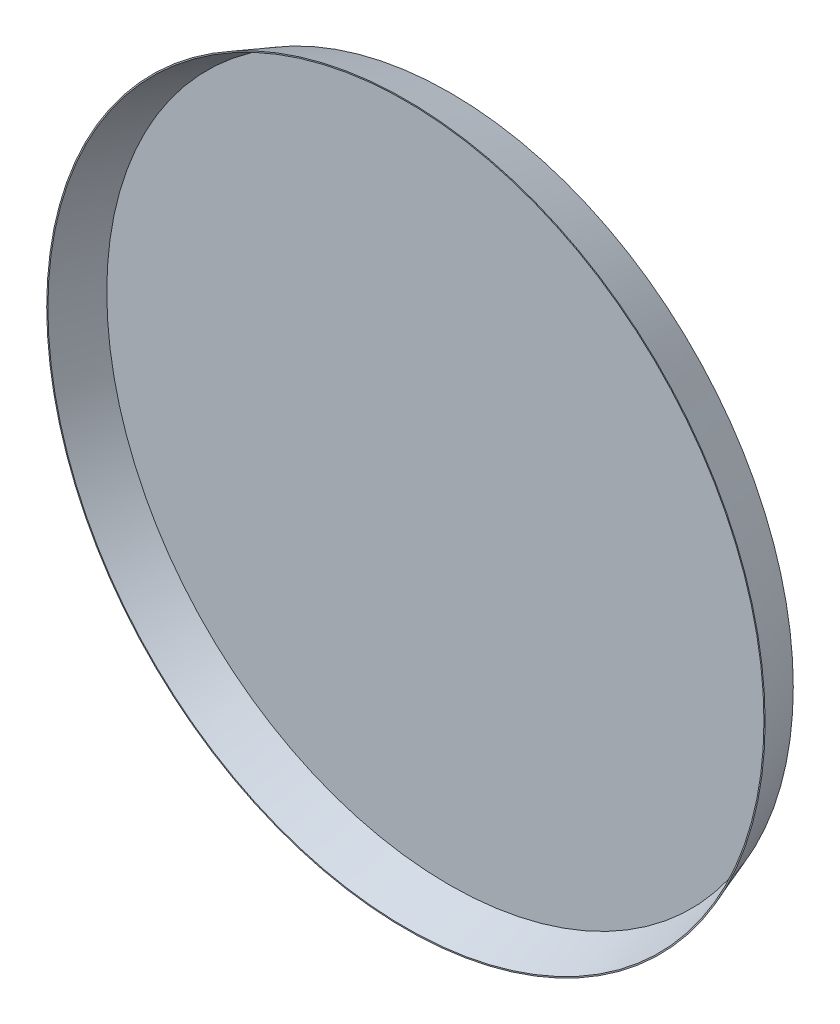
SolidWorks part; units mm, degrees
ref_plane "Front" through (0, 0, 0) normal (0, 0, 1) x (1, 0, 0)
ref_plane "Top" through (0, 0, 0) normal (0, 1, 0) x (1, 0, 0)
ref_plane "Right" through (0, 0, 0) normal (1, 0, 0) x (0, 0, -1)
sketch "Sketch1" plane through (0, 0, 0) normal (0, 0, 1) x (1, 0, 0)
  circle A0 centre (0, 0) radius 15.5
  dimension "D1" = 31
extrude "Base-Extrude" add sketch "Sketch1" along normal blind 2 draft 20 draft outward yes
shell "Shell1" thickness 0.05
sketch "Sketch2" plane through (0, 0, 0.05) normal (0, 0, 1) x (1, 0, 0)
  line L0 (-19.075, 0) -> (20.9062, 0) construction
  line L1 (0, 17.0302) -> (0, -17.1523) construction
  circle A0 centre (10, 0) radius 1.75
  circle A1 centre (-7.5, 0) radius 4.05
  circle A2 centre (0, 7.5) radius 4.05
  circle A3 centre (0, -7.5) radius 4.05
  circle A4 centre (0, 0) radius 0.5
  dimension "D1" = 8.1
  dimension "D2" = 8.1
  dimension "D3" = 8.1
  dimension "D4" = 3.5
  dimension "D5" = 10
  dimension "D6" = 7.5
  dimension "D7" = 7.5
  dimension "D8" = 7.5
  dimension "D9" = 1
extrude "Cut-Extrude1" [suppressed] cut sketch "Sketch2" against normal through all
sketch "Sketch4" plane through (0, 0, 0.05) normal (0, 0, 1) x (1, 0, 0)
  line L0 (0, 0) -> (20, 0) construction
  line L1 (0, 0) -> (17.3205, -10) construction
  line L2 (0, 0) -> (10, -17.3205) construction
  line L3 (0, 0) -> (0, -20) construction
  line L4 (0, 0) -> (-10, -17.3205) construction
  line L5 (0, 0) -> (-17.3205, -10) construction
  line L6 (0, 0) -> (-20, 0) construction
  line L7 (0, 0) -> (-17.3205, 10) construction
  line L8 (0, 0) -> (-10, 17.3205) construction
  line L9 (0, 0) -> (0, 20) construction
  line L10 (0, 0) -> (10, 17.3205) construction
  line L11 (0, 0) -> (17.3205, 10) construction
  circle A0 centre (0, 0) radius 10
  dimension "D1" = 20
  dimension "D2" = 20
sketch "Sketch5" [suppressed] plane through (0, 0, 0.05) normal (0, 0, 1) x (1, 0, 0)
  circle A0 centre (-7.5, 0) radius 0.095
  circle A1 centre (0, -7.5) radius 0.095
  circle A2 centre (0, 7.5) radius 0.095
extrude "Cut-Extrude2" [suppressed] cut sketch "Sketch5" against normal through all
